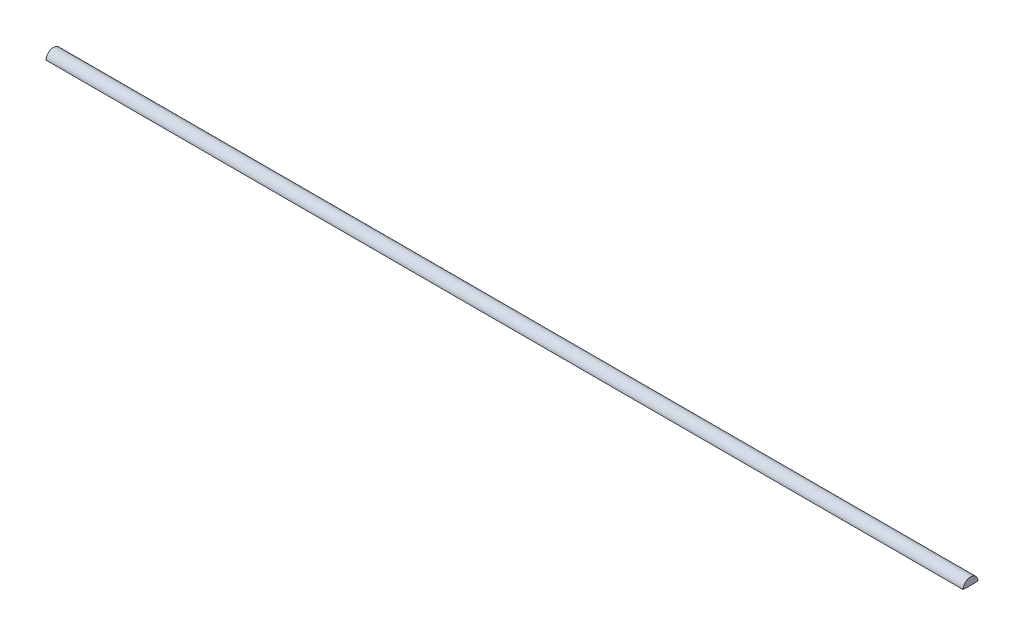
SolidWorks part; units mm, degrees
material "CMR DEFAULT - CHANGE MATERIAL"
ref_plane "XY PLANE - TOP" through (0, 0, 0) normal (0, 0, 1) x (1, 0, 0)
ref_plane "XZ PLANE - SIDE" through (0, 0, 0) normal (0, 1, 0) x (1, 0, 0)
ref_plane "YZ PLANE - FRONT" through (0, 0, 0) normal (1, 0, 0) x (0, 0, -1)
sketch "Sketch1" plane through (0, 0, 0) normal (1, 0, 0) x (0, 0, -1)
  arc A0 (-3.174, -63.4206) -> (3.174, -63.4206) centre (0, 0) ccw
  arc A1 (3.174, -63.4206) -> (-3.174, -63.4206) centre (0, -63.5) ccw
  dimension "D1" = 127
  dimension "D2" = 6.35
extrude "Boss-Extrude1" add sketch "Sketch1" along normal blind 389.89
